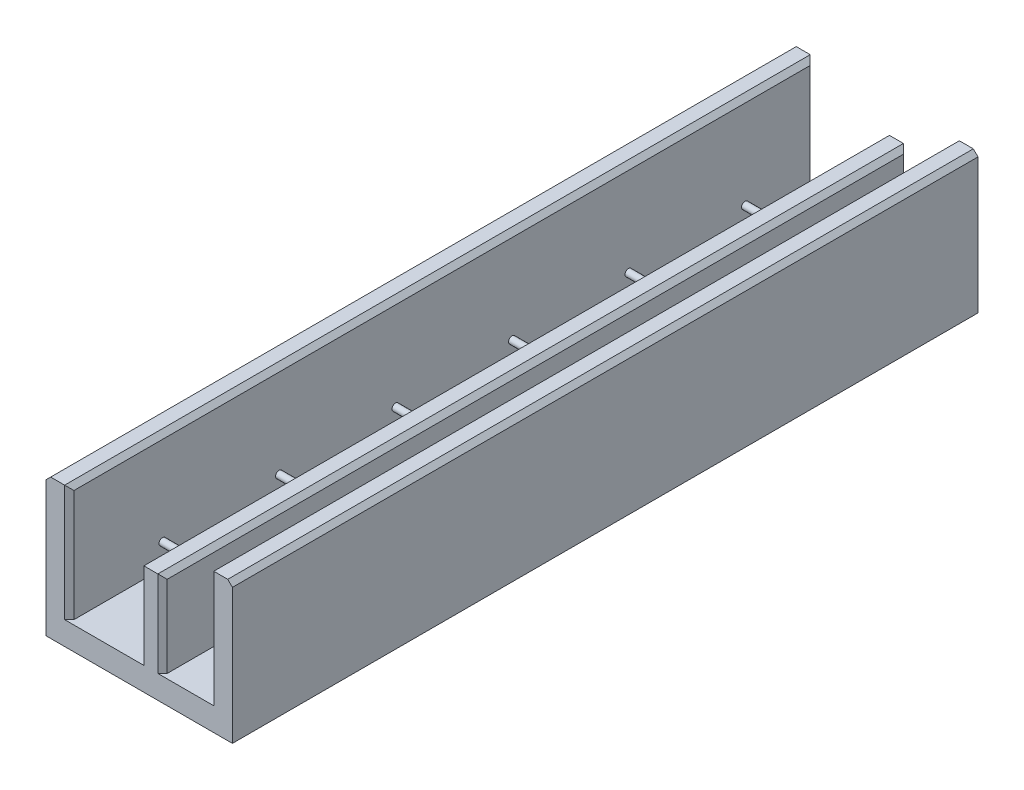
SolidWorks part; units mm, degrees
ref_plane "Alzado" through (0, 0, 0) normal (0, 0, 1) x (1, 0, 0)
ref_plane "Planta" through (0, 0, 0) normal (0, 1, 0) x (1, 0, 0)
ref_plane "Vista lateral" through (0, 0, 0) normal (1, 0, 0) x (0, 0, -1)
sketch "Croquis1" plane through (0, 0, 0) normal (0, 0, 1) x (1, 0, 0)
  line L0 (0, 0) -> (-800, 0)
  line L1 (-800, 0) -> (-800, 600)
  line L2 (-800, 600) -> (-700, 600)
  line L3 (-700, 600) -> (-700, 100)
  line L4 (-700, 100) -> (-400, 100)
  line L5 (-400, 100) -> (-400, 470)
  line L6 (-400, 470) -> (-300, 470)
  line L7 (-300, 470) -> (-300, 100)
  line L8 (-300, 100) -> (-100, 100)
  line L9 (-100, 100) -> (-100, 600)
  line L10 (-100, 600) -> (0, 600)
  line L11 (0, 600) -> (0, 0)
  dimension "D1" = 800
  dimension "D2" = 600
  dimension "D3" = 100
  dimension "D4" = 500
  dimension "D5" = 300
  dimension "D6" = 370
  dimension "D7" = 100
  dimension "D8" = 370
  dimension "D9" = 200
extrude "Saliente-Extruir1" add sketch "Croquis1" along normal blind 3200
chamfer "Chaflán2" distance 20 angle 45 14 edges at (-100, 350, 0) (0, 600, 1600) (-700, 350, 0) (-700, 600, 1600) (-700, 350, 3200) (-100, 350, 3200) (-300, 285, 0) (-300, 285, 3200) (-300, 470, 1600) (-400, 285, 0) (-400, 285, 3200) (-400, 470, 1600) (-800, 600, 1600) (-100, 600, 1600)
sketch "Croquis2" plane through (-800, 0, 0) normal (-1, 0, 0) x (0, 0, 1)
  line L0 (0, 580) -> (0, 0) construction
  circle A0 centre (300, 200) radius 15
  dimension "D3" = 30
  dimension "D1" = 300
extrude "Saliente-Extruir2" add sketch "Croquis2" against normal up to surface (700 mm away) up to face at (-100, 340, 1600)
pattern_linear "MatrizL1" count 6 spacing 500 along (0, 0, 1) of "Saliente-Extruir2"
